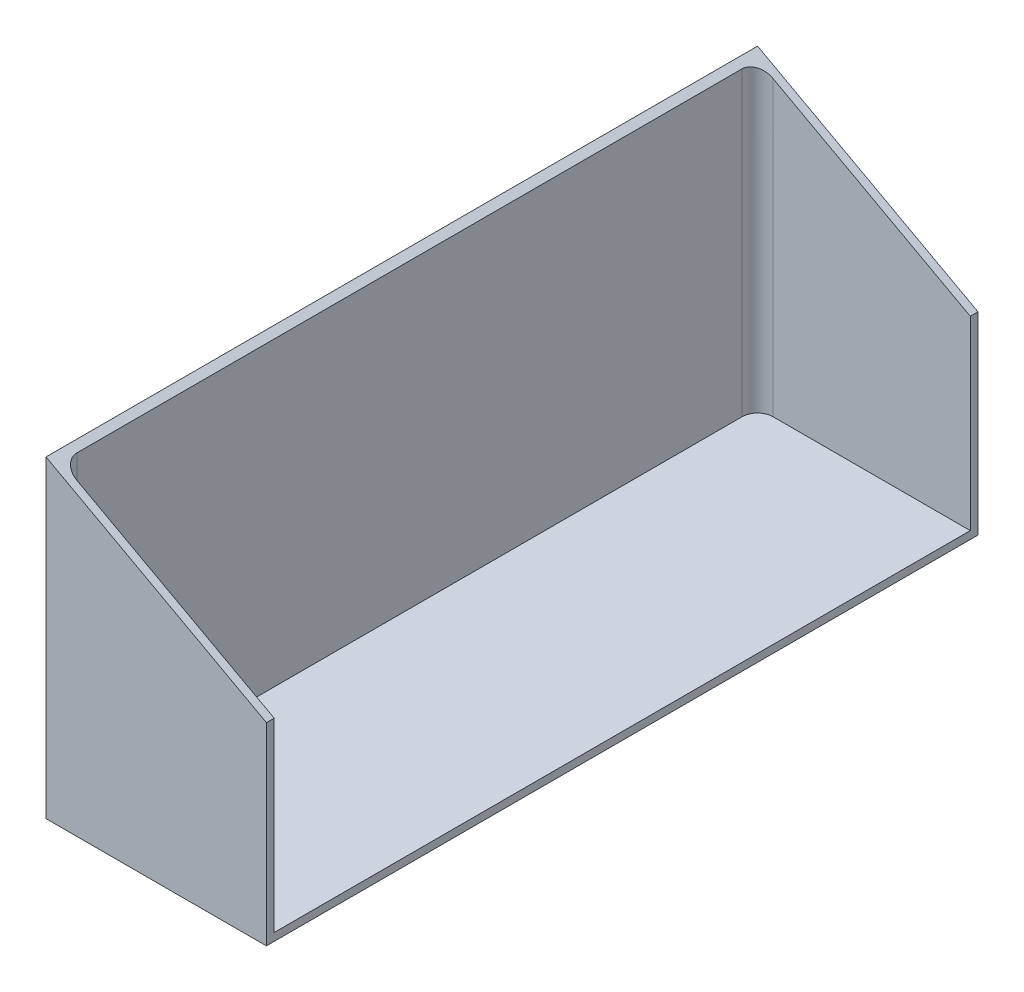
SolidWorks part; units mm, degrees
material "Balsa"
ref_plane "Front Plane" through (0, 0, 0) normal (0, 0, 1) x (1, 0, 0)
ref_plane "Top Plane" through (0, 0, 0) normal (0, 1, 0) x (1, 0, 0)
ref_plane "Right Plane" through (0, 0, 0) normal (1, 0, 0) x (0, 0, -1)
sketch "Sketch1" plane through (0, 0, 0) normal (0, 0, 1) x (1, 0, 0)
  line L0 (0, 405) -> (285, 250)
  line L5 (0, 0) -> (285, 0)
  line L6 (0, 0) -> (0, 405)
  line L8 (285, 0) -> (285, 250)
  dimension "D2" = 405
  dimension "D3" = 250
extrude "Boss-Extrude1" add sketch "Sketch1" against normal blind 10
sketch "Sketch2" plane through (0, 0, 0) normal (0, 0, 1) x (1, 0, 0)
  line L0 (0, 405) -> (0, 0) construction
  line L1 (285, 0) -> (0, 0)
  line L2 (285, 0) -> (285, 10)
  line L3 (285, 10) -> (10, 10)
  line L4 (0, 0) -> (0, 10)
  line L5 (0, 405) -> (10, 399.5614)
  line L6 (0, 0) -> (10, 0)
  line L7 (0, 0) -> (0, 405)
  line L9 (10, 10) -> (10, 399.5614)
  line L10 (285, 250) -> (0, 405) construction
  line M10 (0, 405) -> (0, 0)
  line M11 (0, 0) -> (285, 0)
  line M12 (285, 0) -> (285, 250)
  line M13 (285, 250) -> (0, 405)
  dimension "D1" = 10
  dimension "D2" = 10
extrude "Boss-Extrude2" add sketch "Sketch2" against normal blind 910 contours L3 L9 L1 M13 M10 M11 M12
ref_plane "Symetric 1" through (0, 0, -460) normal (0, 0, -1) x (-1, 0, 0)
mirror "Mirror1" about plane through (0, 0, -460) normal (0, 0, -1) of "Boss-Extrude1"
fillet "Fillet1" radius 20 2 edges at (10, 204.7807, -10) (10, 204.7807, -910)
